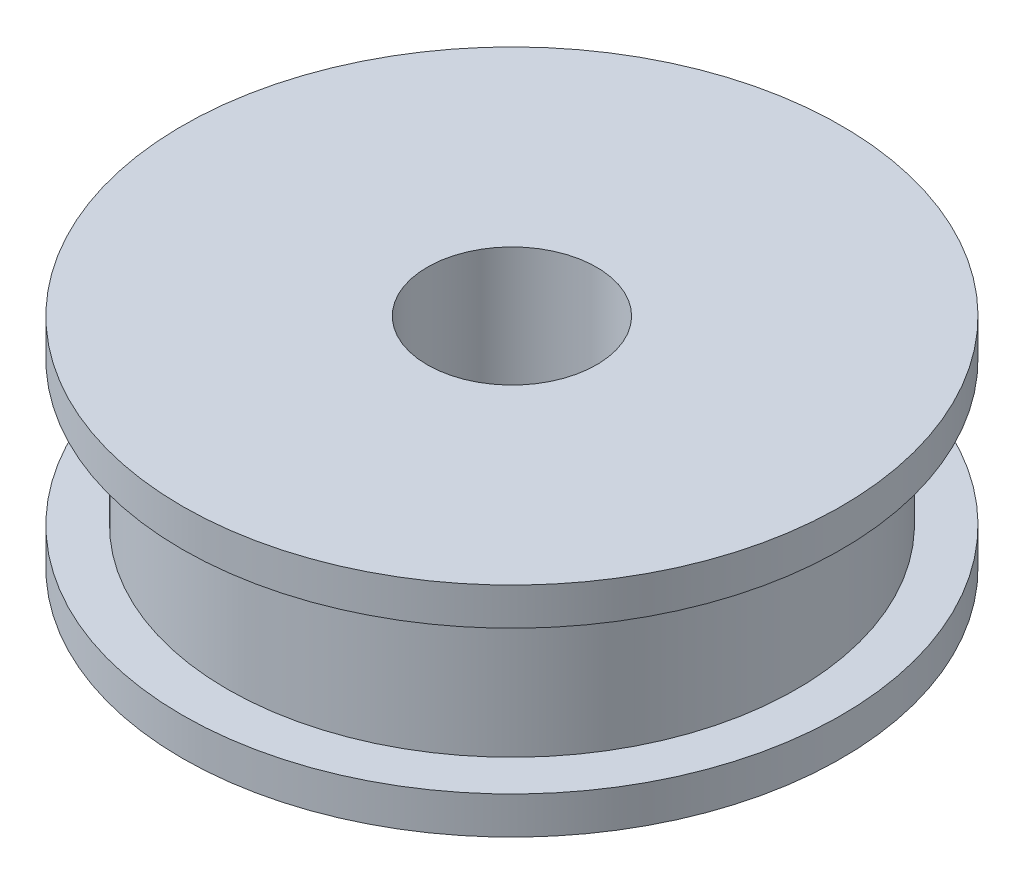
SolidWorks part; units mm, degrees
ref_plane "Front Plane" through (0, 0, 0) normal (0, 0, 1) x (1, 0, 0)
ref_plane "Top Plane" through (0, 0, 0) normal (0, 1, 0) x (1, 0, 0)
ref_plane "Right Plane" through (0, 0, 0) normal (1, 0, 0) x (0, 0, -1)
sketch "Sketch1" plane through (0, 0, 0) normal (0, 1, 0) x (1, 0, 0)
  circle A0 centre (0, 0) radius 11.8682
  dimension "D1" = 23.7363
extrude "Boss-Extrude1" add sketch "Sketch1" along normal blind 1.3462
sketch "Sketch2" plane through (0, 1.3462, 0) normal (0, 1, 0) x (1, 0, 0)
  circle A0 centre (0, 0) radius 10.2489
  dimension "D1" = 20.4978
extrude "Boss-Extrude2" add sketch "Sketch2" along normal blind 5.1689
sketch "Sketch3" plane through (0, 6.5151, 0) normal (0, 1, 0) x (1, 0, 0)
  circle A0 centre (0, 0) radius 11.8682 construction
  circle A1 centre (0, 0) radius 11.8682
extrude "Boss-Extrude4" add sketch "Sketch3" along normal blind 1.3462
sketch "Sketch4" plane through (0, 7.8613, 0) normal (0, 1, 0) x (1, 0, 0)
  circle A0 centre (0, 0) radius 3.048
  dimension "D1" = 6.096
extrude "Cut-Extrude1" cut sketch "Sketch4" against normal through all
